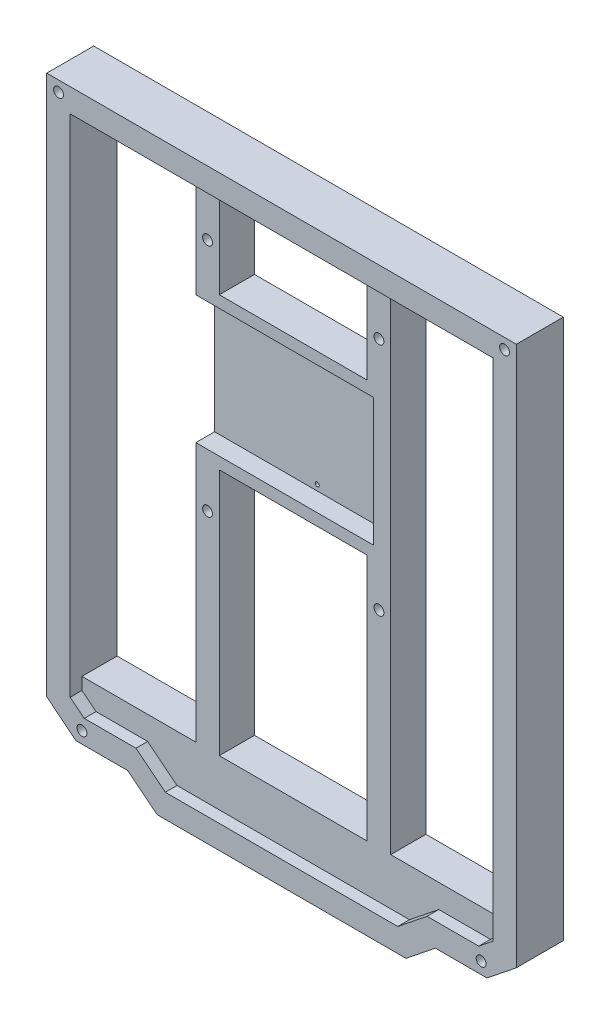
SolidWorks part; units mm, degrees
ref_plane "Plan de face" through (0, 0, 0) normal (0, 0, 1) x (1, 0, 0)
ref_plane "Plan de dessus" through (0, 0, 0) normal (0, 1, 0) x (1, 0, 0)
ref_plane "Plan de droite" through (0, 0, 0) normal (1, 0, 0) x (0, 0, -1)
ref_plane "Plan1" through (0, 0, 106.9027) normal (0, 0, 1) x (1, 0, 0)
sketch "Esquisse1" plane through (0, 0, 106.9027) normal (0, 0, 1) x (1, 0, 0)
  line L0 (88.6441, -133.6995) -> (88.6441, -103.6995)
  line L1 (88.6441, -103.6995) -> (-111.3559, -103.6995)
  line L2 (-111.3559, -103.6995) -> (-111.3559, -133.6995)
  line L3 (-111.3559, -133.6995) -> (88.6441, -133.6995)
extrude "Boss.-Extru.1" add sketch "Esquisse1" against normal blind 20
sketch "Esquisse2" plane through (0, -103.6995, 0) normal (0, 1, 0) x (-1, 0, 0)
  line L0 (52.8559, 86.9027) -> (-30.1441, 86.9027)
  line L1 (-30.1441, 86.9027) -> (-30.1441, 106.9027)
  line L2 (-30.1441, 106.9027) -> (52.8559, 106.9027)
  line L3 (52.8559, 106.9027) -> (52.8559, 86.9027)
extrude "Boss.-Extru.2" add sketch "Esquisse2" along normal blind 170
sketch "Esquisse3" plane through (0, 66.3005, 0) normal (0, 1, 0) x (-1, 0, 0)
  line L0 (-20.1441, 106.9027) -> (-20.1441, 86.9027)
  line L1 (-20.1441, 86.9027) -> (-30.1441, 86.9027)
  line L2 (-30.1441, 86.9027) -> (-30.1441, 106.9027)
  line L3 (-30.1441, 106.9027) -> (-20.1441, 106.9027)
extrude "Boss.-Extru.3" add sketch "Esquisse3" along normal blind 40
sketch "Esquisse4" plane through (0, 66.3005, 0) normal (0, 1, 0) x (-1, 0, 0)
  line L0 (52.8559, 106.9027) -> (52.8559, 86.9027)
  line L1 (52.8559, 86.9027) -> (42.8559, 86.9027)
  line L2 (42.8559, 86.9027) -> (42.8559, 106.9027)
  line L3 (42.8559, 106.9027) -> (52.8559, 106.9027)
extrude "Boss.-Extru.4" add sketch "Esquisse4" along normal blind 40
sketch "Esquisse5" plane through (0, -103.6995, 0) normal (0, 1, 0) x (-1, 0, 0)
  line L0 (-78.6441, 106.9027) -> (-78.6441, 86.9027)
  line L1 (-78.6441, 86.9027) -> (-88.6441, 86.9027)
  line L2 (-88.6441, 86.9027) -> (-88.6441, 106.9027)
  line L3 (-88.6441, 106.9027) -> (-78.6441, 106.9027)
extrude "Boss.-Extru.5" add sketch "Esquisse5" along normal blind 210
sketch "Esquisse6" plane through (0, -103.6995, 0) normal (0, 1, 0) x (-1, 0, 0)
  line L0 (101.3559, 86.9027) -> (101.3559, 106.9027)
  line L1 (101.3559, 106.9027) -> (111.3559, 106.9027)
  line L2 (111.3559, 106.9027) -> (111.3559, 86.9027)
  line L3 (111.3559, 86.9027) -> (101.3559, 86.9027)
extrude "Boss.-Extru.6" add sketch "Esquisse6" along normal blind 210
sketch "Esquisse7" plane through (0, 0, 106.9027) normal (0, 0, 1) x (1, 0, 0)
  line L0 (-42.8559, 106.3005) -> (-52.8559, 106.3005)
  line L1 (-52.8559, 106.3005) -> (-52.8559, -103.6995)
  line L2 (-52.8559, -103.6995) -> (-101.3559, -103.6995)
  line L3 (-101.3559, -103.6995) -> (-101.3559, -113.6995)
  line L4 (-101.3559, -113.6995) -> (-60.8659, -113.6995)
  line L5 (-60.8659, -113.6995) -> (-60.8659, -123.6995)
  line L6 (-60.8659, -123.6995) -> (38.1541, -123.6995)
  line L7 (38.1541, -123.6995) -> (38.1541, -113.6995)
  line L8 (38.1541, -113.6995) -> (78.6441, -113.6995)
  line L9 (78.6441, -113.6995) -> (78.6441, -103.6995)
  line L10 (78.6441, -103.6995) -> (30.1441, -103.6995)
  line L11 (30.1441, -103.6995) -> (30.1441, 106.3005)
  line L12 (30.1441, 106.3005) -> (20.1441, 106.3005)
  line L13 (20.1441, 106.3005) -> (20.1441, 66.3005)
  line L14 (20.1441, 66.3005) -> (-42.8559, 66.3005)
  line L15 (-42.8559, 66.3005) -> (-42.8559, 106.3005)
extrude "Enlèv. mat.-Extru.1" cut sketch "Esquisse7" against normal blind 5
sketch "Esquisse8" plane through (0, 106.3005, 0) normal (0, 1, 0) x (-1, 0, 0)
  line L0 (-88.6441, 86.9027) -> (-88.6441, 106.9027)
  line L1 (-88.6441, 106.9027) -> (111.3559, 106.9027)
  line L2 (111.3559, 106.9027) -> (111.3559, 86.9027)
  line L3 (111.3559, 86.9027) -> (-88.6441, 86.9027)
extrude "Boss.-Extru.7" add sketch "Esquisse8" along normal blind 10
sketch "Esquisse9" plane through (0, 0, 86.9027) normal (0, 0, -1) x (-1, 0, 0)
  line L0 (111.3559, -133.6995) -> (111.3559, -123.6995)
  line L1 (111.3559, -123.6995) -> (64.3759, -123.6995)
  line L2 (64.3759, -123.6995) -> (64.3759, -133.6995)
  line L3 (64.3759, -133.6995) -> (111.3559, -133.6995)
extrude "Enlèv. mat.-Extru.2" cut sketch "Esquisse9" against normal through all
sketch "Esquisse10" plane through (0, 0, 86.9027) normal (0, 0, -1) x (-1, 0, 0)
  line L0 (-88.6441, -133.6995) -> (-41.6641, -133.6995)
  line L1 (-41.6641, -133.6995) -> (-41.6641, -123.6995)
  line L2 (-41.6641, -123.6995) -> (-88.6441, -123.6995)
  line L3 (-88.6441, -123.6995) -> (-88.6441, -133.6995)
extrude "Enlèv. mat.-Extru.3" cut sketch "Esquisse10" against normal through all
sketch "Esquisse11" plane through (0, 0, 101.9027) normal (0, 0, 1) x (1, 0, 0)
  line L0 (20.1441, -103.6995) -> (20.1441, 1.7465)
  line L1 (20.1441, 1.7465) -> (-42.8559, 1.7465)
  line L2 (-42.8559, 1.7465) -> (-42.8559, -103.6995)
  line L3 (-42.8559, -103.6995) -> (20.1441, -103.6995)
extrude "Enlèv. mat.-Extru.4" cut sketch "Esquisse11" against normal through all
sketch "Esquisse12" plane through (-52.8559, 0, 0) normal (-1, 0, 0) x (0, 0, 1)
  line L0 (93.9027, 6.7735) -> (101.9027, 6.7735)
  line L1 (101.9027, 6.7735) -> (101.9027, 61.2735)
  line L2 (101.9027, 61.2735) -> (93.9027, 61.2735)
  line L3 (93.9027, 61.2735) -> (93.9027, 6.7735)
extrude "Enlèv. mat.-Extru.5" cut sketch "Esquisse12" against normal blind 75.65
draft "Dépouille1" type of draft neutral plane draft angle 51.318 faces to draft 2 face at (38.1541, -118.6995, 104.4027) face at (-60.8659, -118.6995, 104.4027) neutral plane through (-60.8659, -123.6995, 101.9027) neutral plane normal (0, 1, 0) parameters "D1"=51.318
draft "Dépouille2" type of draft neutral plane draft angle 51.318 faces to draft 2 face at (41.6641, -128.6995, 96.9027) face at (-64.3759, -128.6995, 96.9027) neutral plane through (-111.3559, -133.6995, 86.9027) neutral plane normal (0, -1, 0) parameters "D1"=51.318
hole_wizard "Diamètre du perçage Ø4.2 (4.2)1" positions "Esquisse14" profile "Esquisse13" hole size "Ø4.2" standard "Ansi Metric"
sketch "Esquisse14" plane through (0, 0, 86.9027) normal (0, 0, -1) x (-1, 0, 0)
  point P0 (-73.6441, -118.6995)
  point P1 (96.3559, -118.6995)
  point P2 (106.3308, 111.8005)
  point P3 (-83.6191, 111.8005)
sketch "Esquisse13" plane through (73.6441, -118.6995, 86.9027) normal (1, 0, 0) x (0, 1, 0)
  line L0 (0, 0) -> (0, 20)
  line L1 (0, 20) -> (2.1, 20)
  line L2 (2.1, 20) -> (2.1, 0)
  line L5 (2.1, 0) -> (0, 0)
  line L11 (0, -6.35) -> (0, 107.95) construction
  dimension "Diamètre du perçage jusqu'au prochain" = 4.2
  dimension "Profondeur du perçage jusqu'au prochain" = 20
hole_wizard "Diamètre du perçage Ø4.2 (4.2)2" positions "Esquisse16" profile "Esquisse15" hole size "Ø4.2" standard "Ansi Metric"
sketch "Esquisse16" plane through (0, 0, 86.9027) normal (0, 0, -1) x (-1, 0, 0)
  point P0 (47.8559, -15.9765)
  point P1 (-25.1441, -15.9765)
  point P2 (-25.1441, 84.0235)
  point P3 (47.8559, 84.0235)
sketch "Esquisse15" plane through (-47.8559, -15.9765, 86.9027) normal (1, 0, 0) x (0, 1, 0)
  line L0 (0, 0) -> (0, 20)
  line L1 (0, 20) -> (2.1, 20)
  line L2 (2.1, 20) -> (2.1, 0)
  line L5 (2.1, 0) -> (0, 0)
  line L11 (0, -6.35) -> (0, 107.95) construction
  dimension "Diamètre du perçage jusqu'au prochain" = 4.2
  dimension "Profondeur du perçage jusqu'au prochain" = 20
hole_wizard "Diamètre du perçage Ø1.75 (1.75)1" positions "Esquisse18" profile "Esquisse17" hole size "Ø1.75" standard "Ansi Metric"
sketch "Esquisse18" plane through (0, 0, 86.9027) normal (0, 0, -1) x (-1, 0, 0)
  point P0 (9.1259, 9.2535)
  point P1 (-20.5641, 34.0235)
  point P2 (9.1259, 58.7935)
sketch "Esquisse17" plane through (-9.1259, 9.2535, 86.9027) normal (1, 0, 0) x (0, 1, 0)
  line L0 (0, 0) -> (0, 20)
  line L1 (0, 20) -> (0.875, 20)
  line L2 (0.875, 20) -> (0.875, 0)
  line L5 (0.875, 0) -> (0, 0)
  line L11 (0, -6.35) -> (0, 107.95) construction
  dimension "Diamètre du perçage jusqu'au prochain" = 1.75
  dimension "Profondeur du perçage jusqu'au prochain" = 20
chamfer "Chanfrein1" distance 12.49 angle 38.682 1 edges at (88.6441, -123.6995, 96.9027)
chamfer "Chanfrein2" distance 10 angle 51.318 1 edges at (-111.3559, -123.6995, 96.9027)
chamfer "Chanfrein3" distance 4.8038 angle 51.318 1 edges at (-101.3559, -113.6995, 104.4027)
chamfer "Chanfrein4" distance 6 angle 38.682 1 edges at (78.6441, -113.6995, 104.4027)
